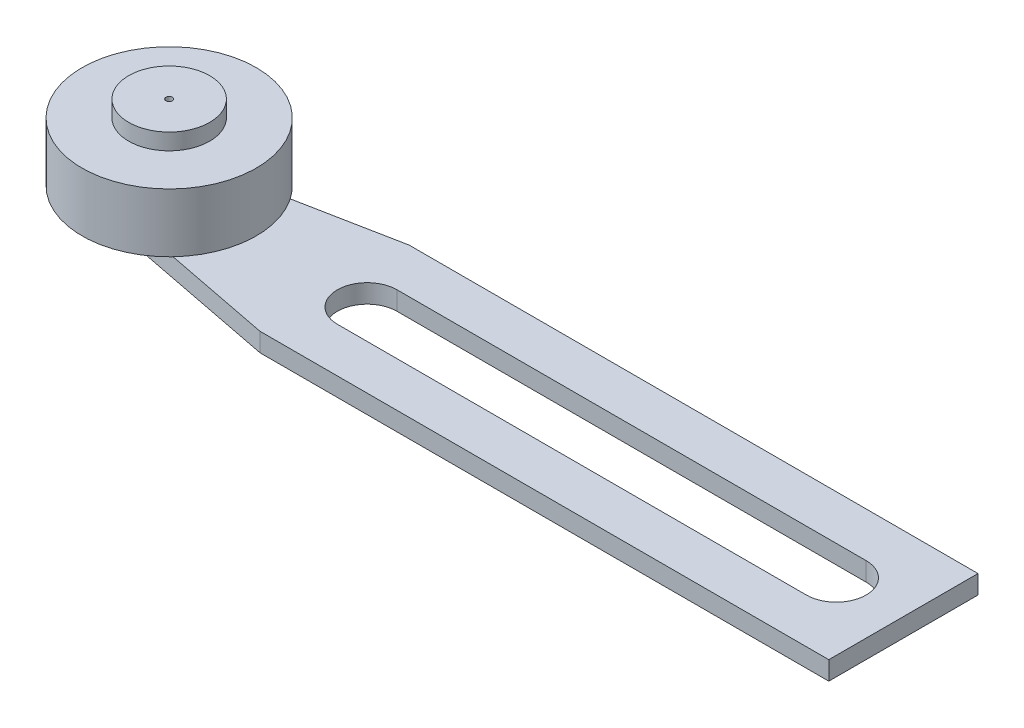
SolidWorks part; units mm, degrees
ref_plane "Front" through (0, 0, 0) normal (0, 0, 1) x (1, 0, 0)
ref_plane "Top" through (0, 0, 0) normal (0, 1, 0) x (1, 0, 0)
ref_plane "Right" through (0, 0, 0) normal (1, 0, 0) x (0, 0, -1)
sketch "Sketch1" plane through (0, 0, 0) normal (0, 1, 0) x (1, 0, 0)
  line L0 (0, 0) -> (-82.9996, -0.0027) construction
  line L1 (-61, 8) -> (0, 8)
  line L3 (-61, -8) -> (0, -8)
  line L4 (0, 8) -> (0, -8)
  line L5 (-79.362, 4.4144) -> (-61, 8)
  line L6 (-79.361, -4.4189) -> (-61, -8)
  line L7 (-57.5, 3.2) -> (-7.2, 3.2)
  line L9 (-7.2, -3.2) -> (-57.5, -3.2)
  arc A0 (-79.362, 4.4144) -> (-79.361, -4.4189) centre (-78.4996, -0.0022) ccw
  arc A1 (-7.2, -3.2) -> (-7.2, 3.2) centre (-7.2, 0) ccw
  arc A2 (-57.5, 3.2) -> (-57.5, -3.2) centre (-57.5, 0) ccw
  dimension "D2" = 4.5
  dimension "D3" = 82.9996
  dimension "D6" = 7.2
  dimension "D1" = 16
  dimension "D4" = 6.4
  dimension "D5" = 61
  dimension "D7" = 57.5
extrude "Extrude1" add sketch "Sketch1" along normal blind 2
sketch "Sketch2" plane through (0, 0, 0) normal (0, 0, 1) x (1, 0, 0)
  line L0 (-78.7343, 1.0659) -> (-78.7343, 17.9195) construction
  line L1 (-76.3929, 0) -> (-75.8429, 0)
  line L3 (-75.8429, 0) -> (-75.8429, -1.3)
  line L4 (-75.8429, -1.3) -> (-78.3929, -1.3)
  line L5 (-78.3929, -1.3) -> (-78.3929, 10.7)
  line L6 (-78.3929, 10.7) -> (-74.3929, 10.7)
  line L7 (-74.3929, 10.7) -> (-74.3929, 8.95)
  line L8 (-74.3929, 8.95) -> (-69.3929, 8.95)
  line L9 (-69.3929, 8.95) -> (-69.3929, 2.65)
  line L10 (-69.3929, 2.65) -> (-75.0094, 2.65)
  line L11 (-75.0094, 2.65) -> (-75.0094, 2)
  line L12 (-75.0094, 2) -> (-76.3929, 2)
  line L13 (-76.3929, 0) -> (-76.3929, 2)
  dimension "D1" = 2.55
  dimension "D2" = 1.3
  dimension "D3" = 12
  dimension "D4" = 2
  dimension "D5" = 4
  dimension "D6" = 1.75
  dimension "D7" = 9
  dimension "D8" = 6.3
  dimension "D9" = 0.65
revolve "Revolve1" add sketch "Sketch2" angle 360 about L0
